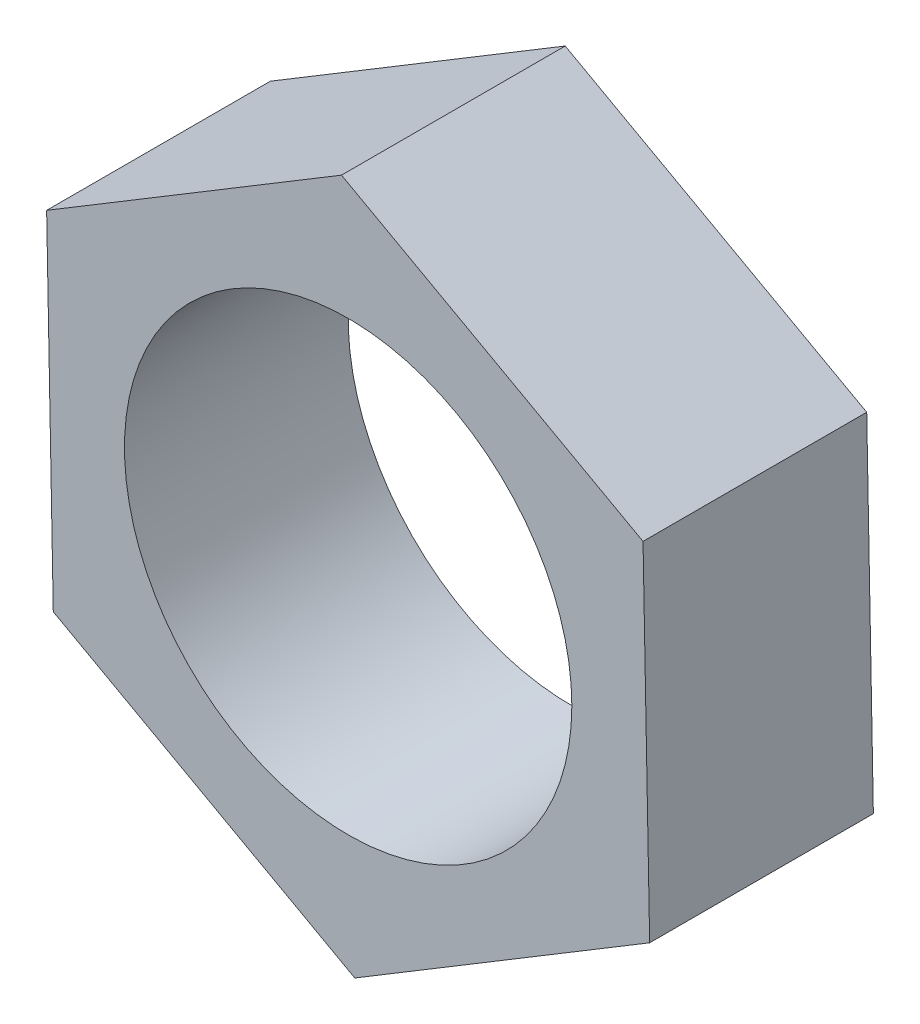
SolidWorks part; units mm, degrees
ref_plane "Front Plane" through (0, 0, 0) normal (0, 0, 1) x (1, 0, 0)
ref_plane "Top Plane" through (0, 0, 0) normal (0, 1, 0) x (1, 0, 0)
ref_plane "Right Plane" through (0, 0, 0) normal (1, 0, 0) x (0, 0, -1)
sketch "Sketch1" plane through (0, 0, 0) normal (0, 0, 1) x (1, 0, 0)
  line L1 (3.9547, 2.3861) -> (-0.0891, 4.6179)
  line L2 (-0.0891, 4.6179) -> (-4.0438, 2.2318)
  line L3 (-4.0438, 2.2318) -> (-3.9547, -2.3861)
  line L4 (-3.9547, -2.3861) -> (0.0891, -4.6179)
  line L5 (0.0891, -4.6179) -> (4.0438, -2.2318)
  line L6 (4.0438, -2.2318) -> (3.9547, 2.3861)
  circle A0 centre (0, 0) radius 4 construction
  dimension "D1" = 8
extrude "Boss-Extrude1" add sketch "Sketch1" along normal blind 3
sketch "Sketch2" plane through (0, 0, 3) normal (0, 0, 1) x (1, 0, 0)
  circle A0 centre (0, 0) radius 3
extrude "Cut-Extrude1" cut sketch "Sketch2" against normal blind 20
